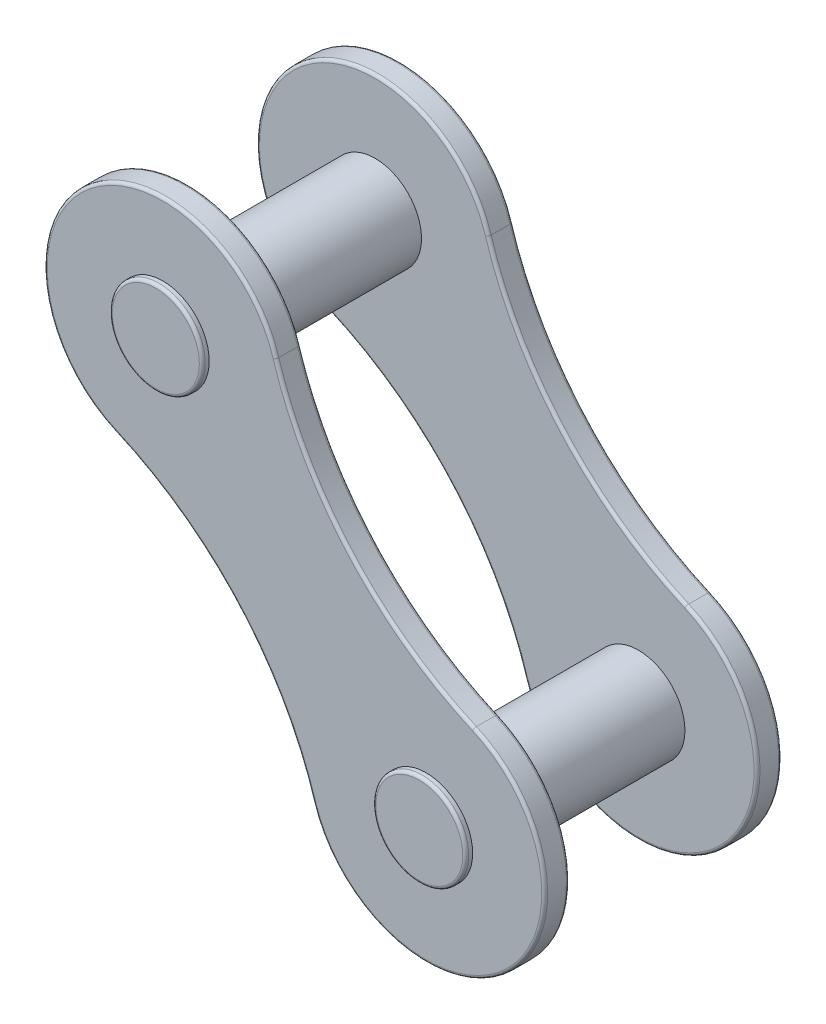
SolidWorks part; units mm, degrees
material "AISI 1020"
ref_plane "Спереди" through (0, 0, 0) normal (0, 0, 1) x (1, 0, 0)
ref_plane "Сверху" through (0, 0, 0) normal (0, 1, 0) x (1, 0, 0)
ref_plane "Справа" through (0, 0, 0) normal (1, 0, 0) x (0, 0, -1)
sketch "Эскиз1" plane through (0, 0, 0) normal (0, 0, 1) x (1, 0, 0)
  line L0 (197.7015, 38.1053) -> (11.6171, 69.2998)
  line L1 (197.7015, -38.1053) -> (11.6171, -69.2998)
  line L3 (46.8644, -52.3559) -> (59.7165, -37.0319)
  line L4 (59.7165, -37.0319) -> (67.7306, -18.7078)
  line L5 (67.7306, -18.7078) -> (70.2576, 1.132)
  line L6 (70.2576, 1.132) -> (67.0928, 20.88)
  line L7 (67.0928, 20.88) -> (58.4925, 38.9364)
  line L8 (58.4925, 38.9364) -> (45.1535, 53.8384)
  line L9 (45.1535, 53.8384) -> (28.1564, 64.3788)
  line L10 (28.1564, 64.3788) -> (8.8783, 69.7036)
  line L11 (8.8783, 69.7036) -> (-11.1191, 69.3814)
  line L12 (-11.1191, 69.3814) -> (-30.2157, 63.4383)
  line L13 (-30.2157, 63.4383) -> (-46.8644, 52.3559)
  line L14 (-46.8644, 52.3559) -> (-59.7165, 37.0319)
  line L15 (-59.7165, 37.0319) -> (-67.7306, 18.7078)
  line L16 (-67.7306, 18.7078) -> (-70.2576, -1.132)
  line L17 (-70.2576, -1.132) -> (-67.0928, -20.88)
  line L18 (-67.0928, -20.88) -> (-58.4925, -38.9364)
  line L19 (-58.4925, -38.9364) -> (-45.1535, -53.8384)
  line L20 (-45.1535, -53.8384) -> (-28.1564, -64.3788)
  line L21 (-28.1564, -64.3788) -> (-8.8783, -69.7036)
  line L22 (-8.8783, -69.7036) -> (11.1191, -69.3814)
  line L23 (11.1191, -69.3814) -> (30.2157, -63.4383)
  line L24 (30.2157, -63.4383) -> (46.8644, -52.3559)
  line L25 (154.7463, -12.4759) -> (165.8834, -29.0881)
  line L26 (165.8834, -29.0881) -> (183.8345, -37.9062)
  line L27 (183.8345, -37.9062) -> (203.7896, -36.5674)
  line L28 (203.7896, -36.5674) -> (220.4018, -25.4303)
  line L29 (220.4018, -25.4303) -> (229.2199, -7.4792)
  line L30 (229.2199, -7.4792) -> (227.8811, 12.4759)
  line L31 (227.8811, 12.4759) -> (216.744, 29.0881)
  line L32 (216.744, 29.0881) -> (198.7929, 37.9062)
  line L33 (198.7929, 37.9062) -> (178.8378, 36.5674)
  line L34 (178.8378, 36.5674) -> (162.2256, 25.4303)
  line L35 (162.2256, 25.4303) -> (153.4075, 7.4792)
  line L36 (153.4075, 7.4792) -> (154.7463, -12.4759)
  arc A0 (11.6171, 69.2998) -> (11.6171, -69.2998) centre (0, 0) ccw
  arc A1 (197.7015, 38.1053) -> (197.7015, -38.1053) centre (191.3137, 0) cw
  circle A2 centre (0, 0) radius 69.5515 construction
  circle A3 centre (191.3137, 0) radius 37.3205 construction
  dimension "D1" = 730
  dimension "D2" = 20
  dimension "D3" = 20
sketch "Эскиз2" plane through (0, 0, 0) normal (0, 0, 1) x (1, 0, 0)
  line L0 (197.7015, 38.1053) -> (11.6171, 69.2998) construction
  line L1 (197.7015, 38.1053) -> (11.6171, 69.2998)
  line L2 (197.7015, -38.1053) -> (11.6171, -69.2998) construction
  line L3 (197.7015, -38.1053) -> (11.6171, -69.2998)
  arc A0 (11.6171, 69.2998) -> (11.6171, -69.2998) centre (0, 0) ccw construction
  arc A1 (11.6171, 69.2998) -> (11.6171, -69.2998) centre (0, 0) ccw
  arc A2 (197.7015, -38.1053) -> (197.7015, 38.1053) centre (191.3137, 0) ccw construction
  arc A3 (197.7015, -38.1053) -> (197.7015, 38.1053) centre (191.3137, 0) ccw
sketch "Эскиз3" plane through (0, 0, 0) normal (0, 0, 1) x (1, 0, 0)
  line L0 (58.4925, 38.9364) -> (45.1535, 53.8384) construction
  circle A2 centre (45.1535, 53.8384) radius 2.5
  circle A3 centre (58.4925, 38.9364) radius 2.5
  circle A4 centre (45.1535, 53.8384) radius 6
  circle A5 centre (58.4925, 38.9364) radius 6
  arc A6 (42.7568, 48.3379) -> (52.7611, 37.1614) centre (35.5668, 31.8363) cw
  arc A7 (50.8849, 55.6135) -> (60.8892, 44.4369) centre (68.0792, 60.9386) ccw
  dimension "D1" = 5
  dimension "D2" = 12
  dimension "D3" = 18
sketch "Эскиз7" plane through (0, 0, 0) normal (0, 0, 1) x (1, 0, 0)
  arc A0 (52.7611, 37.1614) -> (42.7568, 48.3379) centre (35.5668, 31.8363) ccw construction
  arc A1 (52.7611, 37.1614) -> (42.7568, 48.3379) centre (35.5668, 31.8363) ccw
  circle A2 centre (45.1535, 53.8384) radius 6 construction
  arc A3 (50.8849, 55.6135) -> (42.7568, 48.3379) centre (45.1535, 53.8384) ccw
  arc A4 (50.8849, 55.6135) -> (60.8892, 44.4369) centre (68.0792, 60.9386) ccw construction
  arc A5 (50.8849, 55.6135) -> (60.8892, 44.4369) centre (68.0792, 60.9386) ccw
  circle A6 centre (58.4925, 38.9364) radius 6 construction
  arc A7 (52.7611, 37.1614) -> (60.8892, 44.4369) centre (58.4925, 38.9364) ccw
  circle A10 centre (45.1535, 53.8384) radius 2.35
  circle A11 centre (45.1535, 53.8384) radius 2.35
  circle A13 centre (58.4925, 38.9364) radius 2.35
  circle A14 centre (58.4925, 38.9364) radius 2.35
  dimension "D1" = 0.15
  dimension "D2" = 0.15
extrude "Бобышка-Вытянуть3" add sketch "Эскиз7" along normal blind 1.25 from offset 4.75
mirror "Зеркальное отражение3" about plane through (0, 0, 0) normal (0, 0, 1) of bodies 107
sketch "Эскиз8" plane through (0, 0, 0) normal (0, 0, 1) x (1, 0, 0)
  circle A0 centre (45.1535, 53.8384) radius 2.35 construction
  circle A1 centre (45.1535, 53.8384) radius 2.35
  circle A2 centre (58.4925, 38.9364) radius 2.35 construction
  circle A3 centre (58.4925, 38.9364) radius 2.35
extrude "Бобышка-Вытянуть4" add sketch "Эскиз8" along normal mid plane 12.7
fillet "Скругление2" radius 0.15 20 edges at (62.4942, 34.4658, -6) (48.9786, 43.8414, -6) (41.1518, 58.3091, -6) (62.4942, 34.4658, -4.75) (48.9786, 43.8414, -4.75) (41.1518, 58.3091, -4.75) (54.6674, 48.9335, 4.75) (62.4942, 34.4658, 4.75) (48.9786, 43.8414, 4.75) (54.6674, 48.9335, 6) (62.4942, 34.4658, 6) (48.9786, 43.8414, 6) (47.5035, 53.8384, -6.35) (60.8425, 38.9364, -6.35) (54.6674, 48.9335, -6) (54.6674, 48.9335, -4.75) (60.8425, 38.9364, 6.35) (47.5035, 53.8384, 6.35) (41.1518, 58.3091, 4.75) (41.1518, 58.3091, 6)
sketch "Эскиз9" plane through (0, 0, 0) normal (0, 0, 1) x (1, 0, 0)
  circle A0 centre (45.1535, 53.8384) radius 2.5 construction
  circle A1 centre (45.1535, 53.8384) radius 2.5 construction
  circle A2 centre (58.4925, 38.9364) radius 2.5 construction
  circle A3 centre (58.4925, 38.9364) radius 2.5 construction
  circle A4 centre (45.1535, 53.8384) radius 3.5
  circle A5 centre (58.4925, 38.9364) radius 3.5
  dimension "D1" = 1
  dimension "D2" = 1
